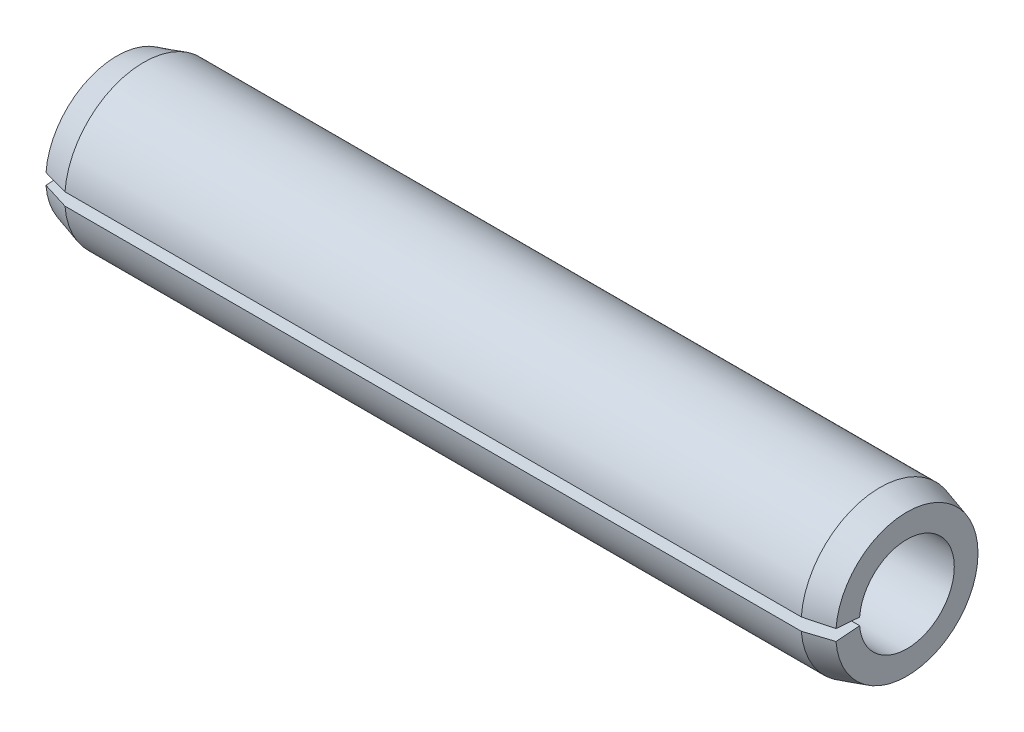
SolidWorks part; units mm, degrees
ref_plane "Plane1" through (0, 0, 0) normal (0, 0, 1) x (1, 0, 0)
ref_plane "Plane2" through (0, 0, 0) normal (0, 1, 0) x (1, 0, 0)
ref_plane "Plane3" through (0, 0, 0) normal (1, 0, 0) x (0, 0, -1)
sketch "Sketch1" plane through (0, 0, 0) normal (0, 0, 1) x (1, 0, 0)
  line L0 (-9.525, 0) -> (111.125, 0) construction
  line L1 (0, 6) -> (100, 6)
  line L2 (100, 6) -> (100, 9)
  line L3 (100, 9) -> (96.6, 10)
  line L4 (96.6, 10) -> (3.4, 10)
  line L5 (3.4, 10) -> (0, 9)
  line L7 (0, 9) -> (0, 6)
  dimension "Diameter" = 20
  dimension "Thickness" = 4
  dimension "Length" = 100
  dimension "Chamfer_len" = 3.4
  dimension "D1" = 18
  dimension "D2" = 18
  dimension "D3" = 3.4
revolve "Base-Revolve" add sketch "Sketch1" angle 360 about L0
sketch "Sketch2" plane through (0, 0, 0) normal (-1, 0, 0) x (0, -1, 0)
  line L0 (0, 0) -> (0.8003, 10.1686)
  line L1 (0, -3.175) -> (0, 12.7) construction
  line L2 (0, 0) -> (-0.8003, 10.1686)
  arc A0 (0.8003, 10.1686) -> (-0.8003, 10.1686) centre (0, 0) ccw
  dimension "Gap_ang" = 9
  dimension "D1" = 10.2
extrude "Gap" cut sketch "Sketch2" against normal through all
equation "\"D1@Sketch2\" = \"Diameter@Sketch1\" * 0.51"
equation "\"D1@Sketch1\" = \"Diameter@Sketch1\" -  ( \"Thickness@Sketch1\" / 2 ) "
equation "\"D2@Sketch1\" = \"D1@Sketch1\""
equation "\"D3@Sketch1\" = \"Chamfer_len@Sketch1\""
